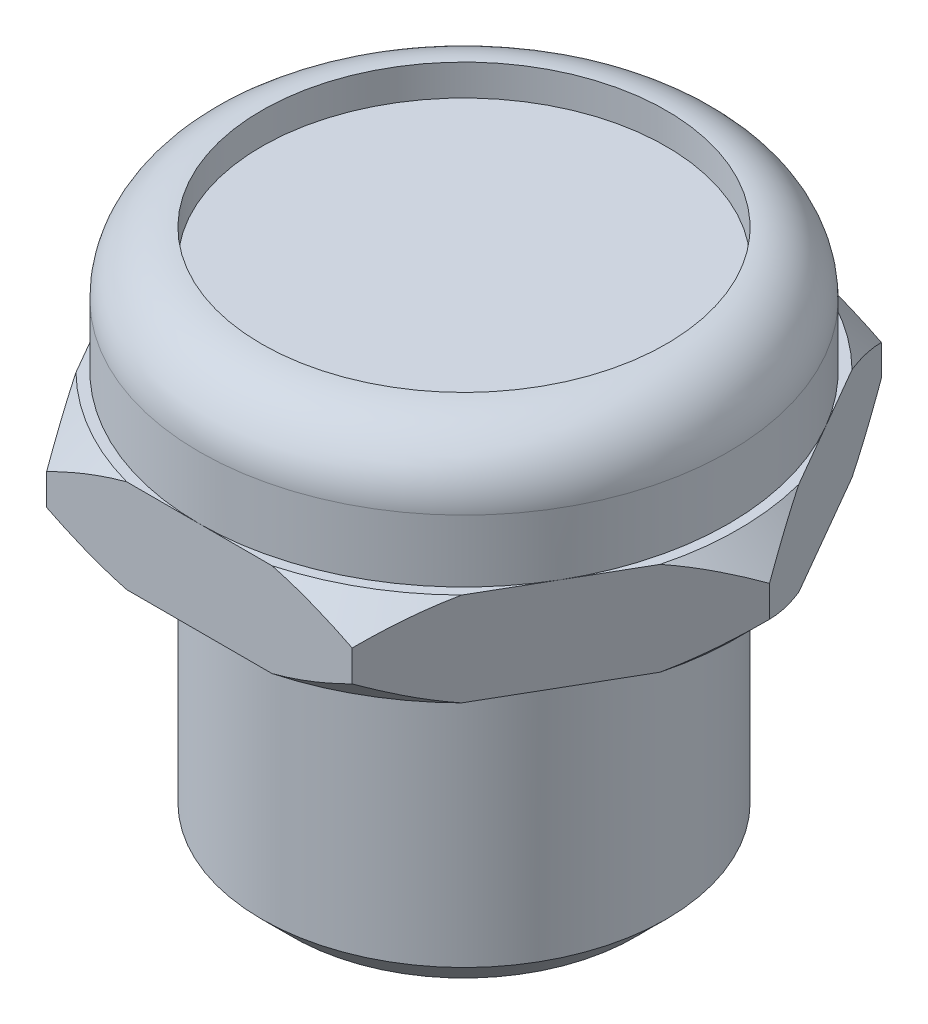
SolidWorks part; units mm, degrees
material "Бронза с оловом"
ref_plane "Спереди" through (0, 0, 0) normal (0, 0, 1) x (1, 0, 0)
ref_plane "Сверху" through (0, 0, 0) normal (0, 1, 0) x (1, 0, 0)
ref_plane "Справа" through (0, 0, 0) normal (1, 0, 0) x (0, 0, -1)
sketch "Эскиз1" plane through (0, 0, 0) normal (0, 1, 0) x (1, 0, 0)
  line L1 (9.815, 0) -> (4.9075, 8.5)
  line L2 (4.9075, 8.5) -> (-4.9075, 8.5)
  line L3 (-4.9075, 8.5) -> (-9.815, 0)
  line L4 (-9.815, 0) -> (-4.9075, -8.5)
  line L5 (-4.9075, -8.5) -> (4.9075, -8.5)
  line L6 (4.9075, -8.5) -> (9.815, 0)
  circle A1 centre (0, 0) radius 8.5 construction
  point P1 (4.9369, 8.483)
  dimension "D1" = 17
extrude "Бобышка-Вытянуть1" add sketch "Эскиз1" along normal blind 3
sketch "Эскиз2" plane through (0, 0, 0) normal (0, 0, 1) x (1, 0, 0)
  line L0 (0, 10.4883) -> (0, -5.2012) construction
  line L1 (9.815, 1.5) -> (11.9188, 1.5) construction
  line L3 (9.815, 3) -> (9.815, 0) construction
  line L4 (9.815, 1) -> (8.815, 0)
  line L5 (4.9075, 0) -> (9.815, 0) construction
  line L6 (9.815, 1) -> (9.815, 0)
  line L7 (9.815, 0) -> (8.815, 0)
  dimension "D1" = 45
  dimension "D2" = 1
revolve "Вырез-Повернуть2" cut sketch "Эскиз2" angle 360 about L0
ref_plane "Плоскость1" through (0, 1.5, 0) normal (0, 1, 0) x (1, 0, 0)
mirror "Зеркальное отражение1" about plane through (0, 1.5, 0) normal (0, 1, 0) of "Вырез-Повернуть2"
sketch "Эскиз3" plane through (0, 3, 0) normal (0, 1, 0) x (1, 0, 0)
  line L0 (6.1936, -6.2724) -> (8.5288, -2.2276) construction
  circle A0 centre (0, 0) radius 8.5
extrude "Бобышка-Вытянуть2" add sketch "Эскиз3" along normal blind 4
fillet "Скругление1" radius 2 1 edges at (0, 7, 8.5)
sketch "Эскиз4" plane through (0, 7, 0) normal (0, 1, 0) x (1, 0, 0)
  circle A1 centre (0, 0) radius 6.5
  circle A2 centre (0, 0) radius 6.5
  dimension "D1" = 0
extrude "Вырез-Вытянуть1" cut sketch "Эскиз4" against normal blind 1
sketch "Эскиз5" plane through (0, 0, 0) normal (0, -1, 0) x (1, 0, 0)
  circle A0 centre (0, 0) radius 6.5
  dimension "D1" = 13
extrude "Бобышка-Вытянуть3" add sketch "Эскиз5" along normal blind 10
cosmetic thread "Условное изображение резьбы1" parameters "D2"=8.566
chamfer "Фаска1" distance 1 angle 45 1 edges at (0, -10, -6.5)
sketch "Эскиз6" plane through (0, -10, 0) normal (0, -1, 0) x (1, 0, 0)
  circle A0 centre (0, 0) radius 4.5
  dimension "D1" = 9
extrude "Вырез-Вытянуть2" cut sketch "Эскиз6" against normal offset from surface (15 mm away) 1 up to face at (0, 6, 6.5)
